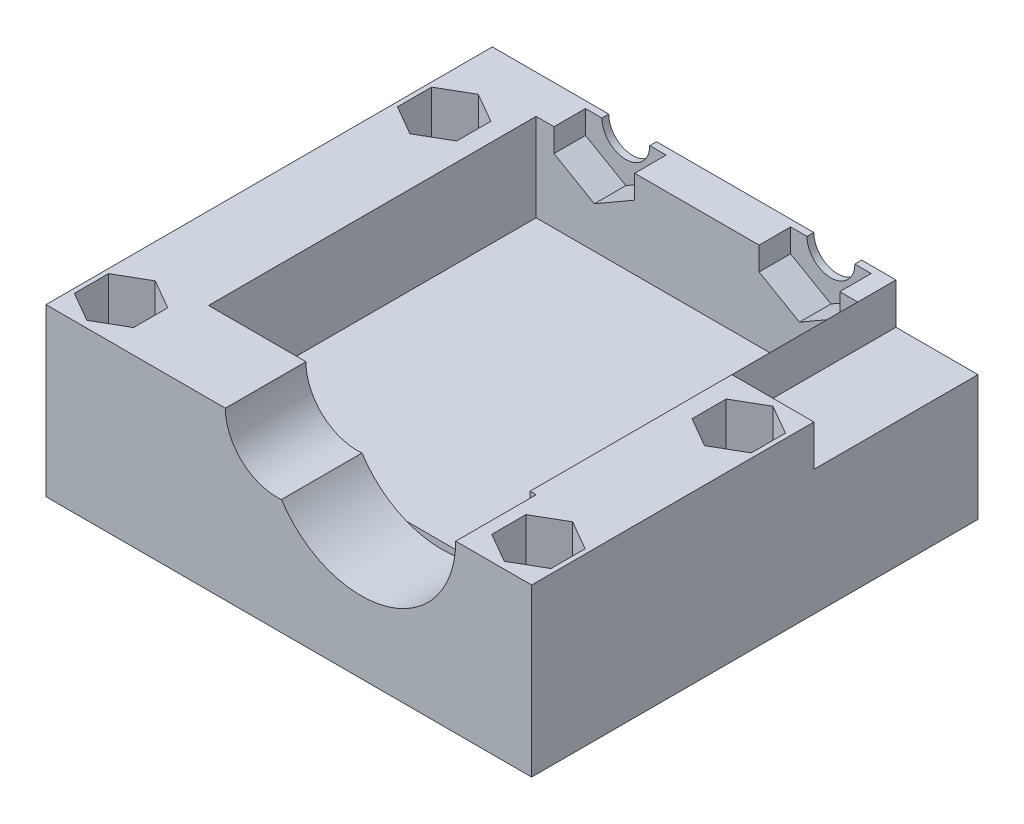
SolidWorks part; units mm, degrees
material "PLA"
ref_plane "Front Plane" through (0, 0, 0) normal (0, 0, 1) x (1, 0, 0)
ref_plane "Top Plane" through (0, 0, 0) normal (0, 1, 0) x (1, 0, 0)
ref_plane "Right Plane" through (0, 0, 0) normal (1, 0, 0) x (0, 0, -1)
sketch "Sketch1" plane through (0, 0, 0) normal (0, 1, 0) x (1, 0, 0)
  line L1 (-16.3195, -14.8159) -> (19.2005, -14.8159)
  line L2 (-16.3195, -14.8159) -> (-16.3195, 17.8341)
  line L3 (-16.3195, 17.8341) -> (19.2005, 17.8341)
  line L4 (19.2005, -14.8159) -> (19.2005, 17.8341)
  dimension "D1" = 32.65
  dimension "D2" = 35.52
extrude "Boss-Extrude1" add sketch "Sketch1" along normal blind 12.17
sketch "Sketch2" plane through (0, 12.17, 0) normal (0, 1, 0) x (1, 0, 0)
  line L0 (-16.3195, -14.8159) -> (-13.8303, -14.8159) construction
  line L1 (-16.3195, -14.8159) -> (19.2005, -14.8159) construction
  line L2 (-13.8303, -14.8159) -> (-13.8303, -14.3159) construction
  line L3 (-13.8303, -14.3159) -> (-13.8303, -9.3159) construction
  line L4 (-6.6935, 0) -> (6.6935, 0) construction
  line L5 (-13.8303, -9.3159) -> (-15.9954, -10.5659)
  line L6 (-15.9954, -10.5659) -> (-15.9954, -13.0659)
  line L7 (-15.9954, -13.0659) -> (-13.8303, -14.3159)
  line L8 (-13.8303, -14.3159) -> (-11.6652, -13.0659)
  line L9 (-11.6652, -13.0659) -> (-11.6652, -10.5659)
  line L10 (-11.6652, -10.5659) -> (-13.8303, -9.3159)
  line L11 (-11.6652, 10.5659) -> (-13.8303, 9.3159)
  line L12 (-11.6652, 13.0659) -> (-11.6652, 10.5659)
  line L13 (-13.8303, 14.3159) -> (-11.6652, 13.0659)
  line L14 (-15.9954, 13.0659) -> (-13.8303, 14.3159)
  line L15 (-15.9954, 10.5659) -> (-15.9954, 13.0659)
  line L16 (-13.8303, 9.3159) -> (-15.9954, 10.5659)
  line L17 (16.7005, 0.3341) -> (16.7005, 5.3341) construction
  line L19 (19.2005, -14.8159) -> (16.7005, -14.8159) construction
  line L20 (16.7005, -14.8159) -> (16.7005, -14.3159) construction
  line L21 (16.7005, -9.3159) -> (16.7005, -14.3159) construction
  line L28 (16.7005, 5.3341) -> (14.5354, 4.0841)
  line L29 (14.5354, 4.0841) -> (14.5354, 1.5841)
  line L36 (16.7005, -14.3159) -> (18.8656, -13.0659)
  line L37 (18.8656, -13.0659) -> (18.8656, -10.5659)
  line L42 (18.8656, -10.5659) -> (16.7005, -9.3159)
  line L43 (16.7005, -9.3159) -> (14.5354, -10.5659)
  line L44 (14.5354, -10.5659) -> (14.5354, -13.0659)
  line L45 (14.5354, -13.0659) -> (16.7005, -14.3159)
  line L46 (16.7005, -9.3159) -> (16.7005, 0.3341) construction
  line L47 (14.5354, 1.5841) -> (16.7005, 0.3341)
  line L48 (16.7005, 0.3341) -> (18.8656, 1.5841)
  line L49 (18.8656, 1.5841) -> (18.8656, 4.0841)
  line L50 (18.8656, 4.0841) -> (16.7005, 5.3341)
  circle A0 centre (-13.8303, -11.8159) radius 2.1651 construction
  circle A2 centre (16.7005, 2.8341) radius 2.1651 construction
  circle A3 centre (16.7005, -11.8159) radius 2.1651 construction
  dimension "D1" = 2.4892
  dimension "D2" = 0.5
  dimension "D3" = 5
  dimension "D4" = 5
  dimension "D5" = 2.5
extrude "Cut-Extrude1" cut sketch "Sketch2" against normal blind 5.25 and the other way through all
sketch "Sketch3" plane through (0, 12.17, 0) normal (0, 1, 0) x (1, 0, 0)
  line L1 (19.2005, 17.8341) -> (13.2005, 17.8341)
  line L2 (19.2005, 17.8341) -> (19.2005, 5.8341)
  line L3 (19.2005, 5.8341) -> (13.2005, 5.8341)
  line L4 (13.2005, 17.8341) -> (13.2005, 5.8341)
  dimension "D1" = 6
  dimension "D2" = 12
extrude "Cut-Extrude2" cut sketch "Sketch3" against normal blind 3
sketch "Sketch4" plane through (0, 12.17, 0) normal (0, 1, 0) x (1, 0, 0)
  line L1 (-10.3195, -8.9259) -> (13.2005, -8.9259)
  line L2 (-10.3195, -8.9259) -> (-10.3195, 15.0341)
  line L3 (-10.3195, 15.0341) -> (13.2005, 15.0341)
  line L4 (13.2005, -8.9259) -> (13.2005, 15.0341)
  line L5 (-10.3195, -8.9259) -> (13.2005, 15.0341) construction
  line L6 (-10.3195, 15.0341) -> (13.2005, -8.9259) construction
  line L8 (-10.3195, -8.9259) -> (-10.3195, -14.8159) construction
  line L9 (-16.3195, -14.8159) -> (19.2005, -14.8159) construction
  line L13 (-10.3195, -14.8159) -> (-16.3195, -14.8159) construction
  line L14 (19.2005, 5.8341) -> (19.2005, 17.8341) construction
  line L15 (19.2005, 5.8341) -> (19.2005, 17.8341)
  dimension "D1" = 23.52
  dimension "D2" = 23.96
  dimension "D3" = 6
  dimension "D4" = 5.89
extrude "Cut-Extrude3" cut sketch "Sketch4" against normal blind 6.425 contours L1 L4 L3 L2
sketch "Sketch6" plane through (0, 0, 14.8159) normal (0, 0, 1) x (1, 0, 0)
  line L0 (19.2005, 12.17) -> (13.6505, 12.17) construction
  line L1 (-16.3195, 12.17) -> (19.2005, 12.17) construction
  line L2 (19.2005, 12.17) -> (6.7309, 12.17) construction
  line L3 (-16.3195, 12.17) -> (-3.1995, 12.17) construction
  line L4 (-3.1995, 12.17) -> (0.5505, 12.17) construction
  arc A4 (0.9047, 8.4368) -> (0.9047, 15.9032) centre (6.7309, 12.17) ccw
  arc A6 (0.9047, 15.9032) -> (0.9047, 8.4368) centre (0.5505, 12.17) ccw
  dimension "D1" = 5.55
  dimension "D2" = 12.4696
  dimension "D3" = 13.12
extrude "Cut-Extrude5" cut sketch "Sketch6" against normal up to surface (5.89 mm away) up to face at (1.4405, 8.9575, 8.9259)
sketch "Sketch7" plane through (0, 0, -15.0341) normal (0, 0, 1) x (1, 0, 0)
  line L0 (19.2005, 12.17) -> (8.9405, 12.17) construction
  line L1 (-10.3195, 12.17) -> (13.2005, 12.17) construction
  line L3 (8.9405, 8.7636) -> (11.8905, 10.4668)
  line L4 (11.8905, 10.4668) -> (11.8905, 13.8732)
  line L5 (11.8905, 13.8732) -> (8.9405, 15.5764)
  line L6 (8.9405, 15.5764) -> (5.9905, 13.8732)
  line L7 (5.9905, 13.8732) -> (5.9905, 10.4668)
  line L8 (5.9905, 10.4668) -> (8.9405, 8.7636)
  line L9 (8.9405, 12.17) -> (-6.0595, 12.17) construction
  line L16 (-6.0595, 12.17) -> (-6.0595, 8.7636) construction
  line L18 (-6.0595, 8.7636) -> (-3.1095, 10.4668)
  line L19 (-3.1095, 10.4668) -> (-3.1095, 13.8732)
  line L20 (-3.1095, 13.8732) -> (-6.0595, 15.5764)
  line L21 (-6.0595, 15.5764) -> (-9.0095, 13.8732)
  line L22 (-9.0095, 13.8732) -> (-9.0095, 10.4668)
  line L23 (-9.0095, 10.4668) -> (-6.0595, 8.7636)
  circle A0 centre (8.9405, 12.17) radius 2.95 construction
  circle A2 centre (-6.0595, 12.17) radius 2.95 construction
  dimension "D1" = 10.26
  dimension "D2" = 3.4064
  dimension "D3" = 3.4064
extrude "Cut-Extrude6" cut sketch "Sketch7" against normal blind 2.3
sketch "Sketch8" plane through (0, 0, -17.8341) normal (0, 0, -1) x (-1, 0, 0)
  line L0 (16.3195, 12.17) -> (6.0595, 12.17) construction
  line L1 (-13.2005, 12.17) -> (16.3195, 12.17) construction
  line L4 (-19.2005, 12.17) -> (-8.9405, 12.17) construction
  circle A1 centre (-8.9405, 12.17) radius 1.75
  circle A2 centre (6.0595, 12.17) radius 1.75
  dimension "D3" = 3.5
  dimension "D4" = 3.5
  dimension "D1" = 10.26
  dimension "D2" = 10.26
extrude "Cut-Extrude7" cut sketch "Sketch8" against normal up to surface (2.8 mm away) up to face at (1.4405, 10.2789, -15.0341)
